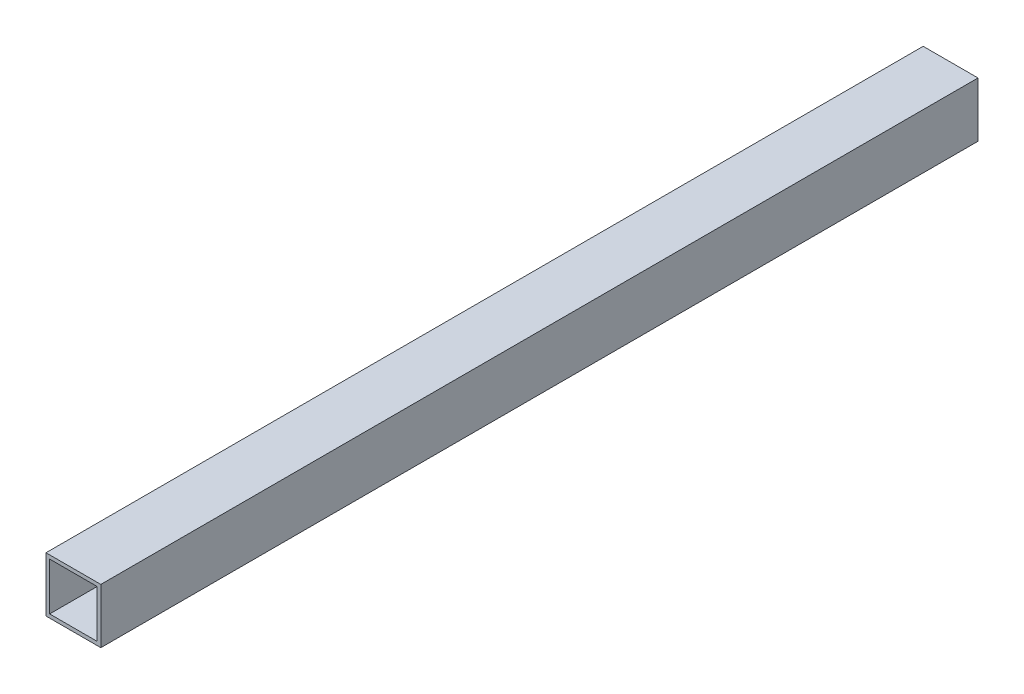
SolidWorks part; units mm, degrees
ref_plane "Front Plane" through (0, 0, 0) normal (0, 0, 1) x (1, 0, 0)
ref_plane "Top Plane" through (0, 0, 0) normal (0, 1, 0) x (1, 0, 0)
ref_plane "Right Plane" through (0, 0, 0) normal (1, 0, 0) x (0, 0, -1)
sketch "Sketch1" plane through (0, 0, 0) normal (0, 0, 1) x (1, 0, 0)
  line L0 (-11.8872, 17.272) -> (-14.478, 17.272) construction
  line L1 (-11.8872, 11.8872) -> (-11.8872, 17.272) construction
  line L2 (-17.272, 11.8872) -> (-11.8872, 11.8872) construction
  line L3 (-17.272, 14.478) -> (-17.272, 11.8872) construction
  line L4 (14.478, 17.272) -> (11.8872, 17.272) construction
  line L5 (17.272, 11.8872) -> (17.272, 14.478) construction
  line L6 (11.8872, 11.8872) -> (17.272, 11.8872) construction
  line L7 (11.8872, 17.272) -> (11.8872, 11.8872) construction
  line L8 (11.8872, -17.272) -> (14.478, -17.272) construction
  line L9 (11.8872, -11.8872) -> (11.8872, -17.272) construction
  line L10 (17.272, -11.8872) -> (11.8872, -11.8872) construction
  line L11 (17.272, -14.478) -> (17.272, -11.8872) construction
  line L12 (-14.478, -17.272) -> (-11.8872, -17.272) construction
  line L13 (-17.272, -11.8872) -> (-17.272, -14.478) construction
  line L14 (-11.8872, -11.8872) -> (-17.272, -11.8872) construction
  line L15 (-11.8872, -17.272) -> (-11.8872, -11.8872) construction
  line L16 (-6.731, 4.5757) -> (-6.731, -4.5757) construction
  line L17 (-6.731, -4.5757) -> (-12.4423, -10.287) construction
  line L18 (-12.4423, -10.287) -> (-15.6718, -10.287) construction
  line L19 (-15.6718, -10.287) -> (-15.6718, -6.858) construction
  line L20 (-15.6718, -6.858) -> (-14.478, -6.858) construction
  line L21 (-14.478, -6.858) -> (-14.478, -4.064) construction
  line L22 (-14.478, -4.064) -> (-19.05, -4.064) construction
  line L23 (-19.05, -4.064) -> (-19.05, -15.875) construction
  line L24 (-15.875, -19.05) -> (-4.064, -19.05) construction
  line L25 (-4.064, -19.05) -> (-4.064, -14.478) construction
  line L26 (-4.064, -14.478) -> (-6.858, -14.478) construction
  line L27 (-6.858, -14.478) -> (-6.858, -15.6718) construction
  line L28 (-6.858, -15.6718) -> (-10.287, -15.6718) construction
  line L29 (-10.287, -15.6718) -> (-10.287, -12.4423) construction
  line L30 (-10.287, -12.4423) -> (-4.5757, -6.731) construction
  line L31 (-4.5757, -6.731) -> (4.5757, -6.731) construction
  line L32 (4.5757, -6.731) -> (10.287, -12.4423) construction
  line L33 (10.287, -12.4423) -> (10.287, -15.6718) construction
  line L34 (10.287, -15.6718) -> (6.858, -15.6718) construction
  line L35 (6.858, -15.6718) -> (6.858, -14.478) construction
  line L36 (6.858, -14.478) -> (4.064, -14.478) construction
  line L37 (4.064, -14.478) -> (4.064, -19.05) construction
  line L38 (4.064, -19.05) -> (15.875, -19.05) construction
  line L39 (19.05, -15.875) -> (19.05, -4.064) construction
  line L40 (19.05, -4.064) -> (14.478, -4.064) construction
  line L41 (14.478, -4.064) -> (14.478, -6.858) construction
  line L42 (14.478, -6.858) -> (15.6718, -6.858) construction
  line L43 (15.6718, -6.858) -> (15.6718, -10.287) construction
  line L44 (15.6718, -10.287) -> (12.4423, -10.287) construction
  line L45 (12.4423, -10.287) -> (6.731, -4.5757) construction
  line L46 (6.731, -4.5757) -> (6.731, 4.5757) construction
  line L47 (6.731, 4.5757) -> (12.4423, 10.287) construction
  line L48 (12.4423, 10.287) -> (15.6718, 10.287) construction
  line L49 (15.6718, 10.287) -> (15.6718, 6.858) construction
  line L50 (15.6718, 6.858) -> (14.478, 6.858) construction
  line L51 (14.478, 6.858) -> (14.478, 4.064) construction
  line L52 (14.478, 4.064) -> (19.05, 4.064) construction
  line L53 (19.05, 4.064) -> (19.05, 15.875) construction
  line L54 (15.875, 19.05) -> (4.064, 19.05) construction
  line L55 (4.064, 19.05) -> (4.064, 14.478) construction
  line L56 (4.064, 14.478) -> (6.858, 14.478) construction
  line L57 (6.858, 14.478) -> (6.858, 15.6718) construction
  line L58 (6.858, 15.6718) -> (10.287, 15.6718) construction
  line L59 (10.287, 15.6718) -> (10.287, 12.4423) construction
  line L60 (10.287, 12.4423) -> (4.5757, 6.731) construction
  line L61 (4.5757, 6.731) -> (-4.5757, 6.731) construction
  line L62 (-4.5757, 6.731) -> (-10.287, 12.4423) construction
  line L63 (-10.287, 12.4423) -> (-10.287, 15.6718) construction
  line L64 (-10.287, 15.6718) -> (-6.858, 15.6718) construction
  line L65 (-6.858, 15.6718) -> (-6.858, 14.478) construction
  line L66 (-6.858, 14.478) -> (-4.064, 14.478) construction
  line L67 (-4.064, 14.478) -> (-4.064, 19.05) construction
  line L68 (-4.064, 19.05) -> (-15.875, 19.05) construction
  line L69 (-19.05, 15.875) -> (-19.05, 4.064) construction
  line L70 (-19.05, 4.064) -> (-14.478, 4.064) construction
  line L71 (-14.478, 4.064) -> (-14.478, 6.858) construction
  line L72 (-14.478, 6.858) -> (-15.6718, 6.858) construction
  line L73 (-15.6718, 6.858) -> (-15.6718, 10.287) construction
  line L74 (-15.6718, 10.287) -> (-12.4423, 10.287) construction
  line L75 (-12.4423, 10.287) -> (-6.731, 4.5757) construction
  line L77 (-9.525, 9.525) -> (9.525, 9.525)
  line L78 (-9.525, 9.525) -> (-9.525, -9.525)
  line L79 (-9.525, -9.525) -> (9.525, -9.525)
  line L80 (9.525, 9.525) -> (9.525, -9.525)
  line L81 (-9.525, 9.525) -> (9.525, -9.525) construction
  line L82 (-9.525, -9.525) -> (9.525, 9.525) construction
  line L83 (-8.255, 8.255) -> (8.255, 8.255)
  line L84 (-8.255, 8.255) -> (-8.255, -8.255)
  line L85 (-8.255, -8.255) -> (8.255, -8.255)
  line L86 (8.255, 8.255) -> (8.255, -8.255)
  line L87 (-8.255, 8.255) -> (8.255, -8.255) construction
  line L88 (-8.255, -8.255) -> (8.255, 8.255) construction
  circle A0 centre (0, 0) radius 3.2639 construction
  arc A1 (-19.05, -15.875) -> (-15.875, -19.05) centre (-15.875, -15.875) ccw construction
  arc A2 (15.875, -19.05) -> (19.05, -15.875) centre (15.875, -15.875) ccw construction
  arc A3 (19.05, 15.875) -> (15.875, 19.05) centre (15.875, 15.875) ccw construction
  arc A4 (-15.875, 19.05) -> (-19.05, 15.875) centre (-15.875, 15.875) ccw construction
  arc A5 (-14.478, 17.272) -> (-17.272, 14.478) centre (-14.478, 14.478) ccw construction
  arc A6 (17.272, 14.478) -> (14.478, 17.272) centre (14.478, 14.478) ccw construction
  arc A7 (14.478, -17.272) -> (17.272, -14.478) centre (14.478, -14.478) ccw construction
  arc A8 (-17.272, -14.478) -> (-14.478, -17.272) centre (-14.478, -14.478) ccw construction
  dimension "D1" = 19.05
  dimension "D2" = 19.05
  dimension "D3" = 1.27
extrude "Boss-Extrude1" add sketch "Sketch1" along normal mid plane 3048
sketch "Sketch2" plane through (9.525, 0, 0) normal (1, 0, 0) x (0, 0, -1)
  line L0 (-1524, 9.525) -> (1524, 9.525) construction
  line L1 (-1524, -9.525) -> (1219.2, -9.525)
  line L2 (-1524, -9.525) -> (-1524, 9.525)
  line L3 (-1524, 9.525) -> (1219.2, 9.525)
  line L4 (1219.2, -9.525) -> (1219.2, 9.525)
  dimension "D1" = 304.8
extrude "Cut-Extrude1" cut sketch "Sketch2" against normal through all
